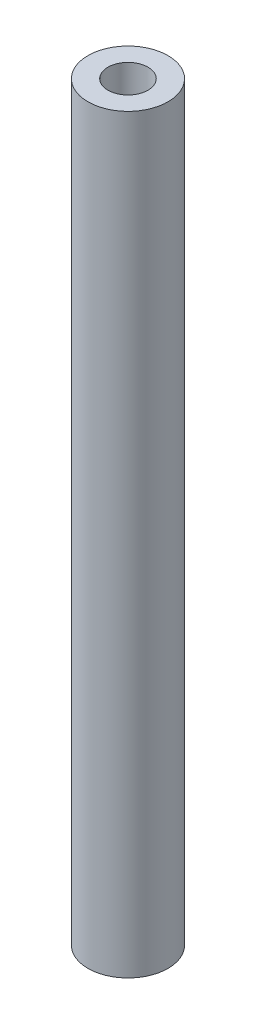
SolidWorks part; units mm, degrees
ref_plane "Front Plane" through (0, 0, 0) normal (0, 0, 1) x (1, 0, 0)
ref_plane "Top Plane" through (0, 0, 0) normal (0, 1, 0) x (1, 0, 0)
ref_plane "Right Plane" through (0, 0, 0) normal (1, 0, 0) x (0, 0, -1)
sketch "Sketch1" plane through (0, 0, 0) normal (0, 1, 0) x (1, 0, 0)
  circle A0 centre (0, 0) radius 4
extrude "Boss-Extrude1" add sketch "Sketch1" along normal mid plane 75
sketch "Sketch2" plane through (0, 37.5, 0) normal (0, 1, 0) x (1, 0, 0)
  circle A0 centre (0, 0) radius 2
extrude "Cut-Extrude1" cut sketch "Sketch2" against normal blind 4
sketch "Sketch3" plane through (0, -37.5, 0) normal (0, -1, 0) x (1, 0, 0)
  circle A0 centre (0, 0) radius 2
extrude "Cut-Extrude2" cut sketch "Sketch3" against normal blind 4
